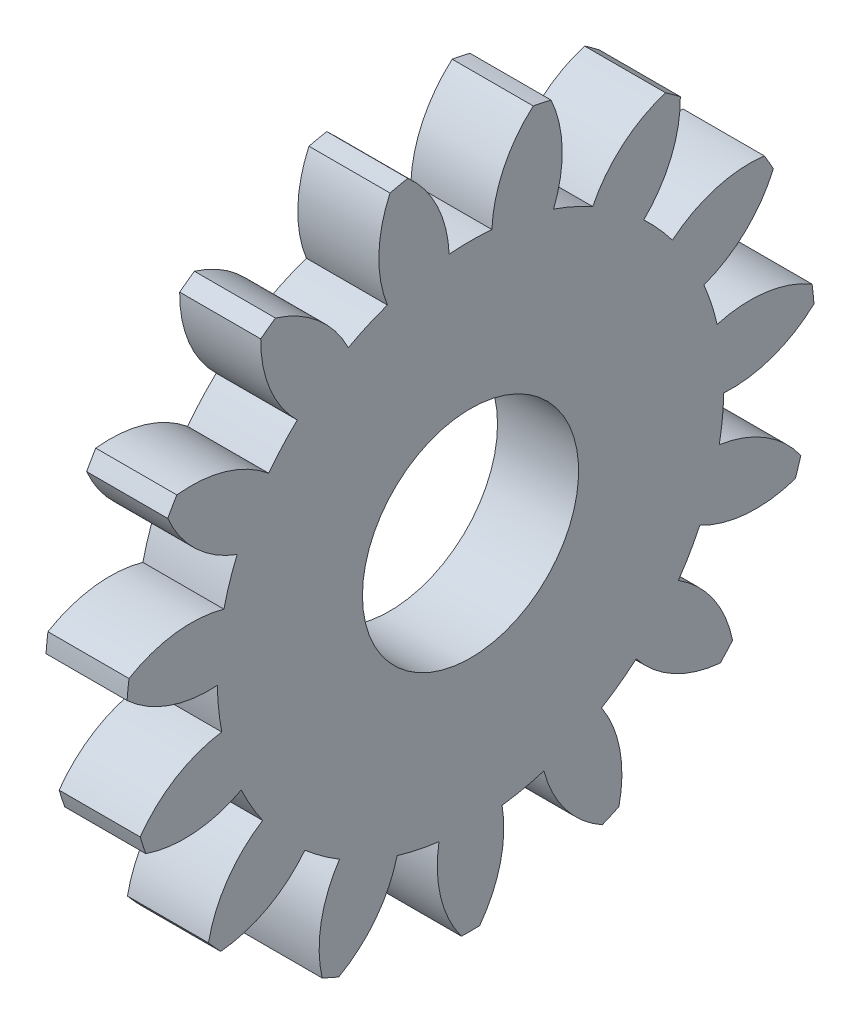
SolidWorks part; units mm, degrees
ref_plane "Plane1" through (0, 0, 0) normal (0, 0, 1) x (1, 0, 0)
ref_plane "Plane2" through (0, 0, 0) normal (0, 1, 0) x (1, 0, 0)
ref_plane "Plane3" through (0, 0, 0) normal (1, 0, 0) x (0, 0, -1)
sketch "HoldingSke" plane through (0, 0, 0) normal (0, 1, 0) x (1, 0, 0)
  line L0 (0, 0) -> (0.644, -0.1725)
  line L1 (-15, 0) -> (100, 0) construction
  line L2 (0, 0) -> (-2.1039, 2.3779)
  line L3 (0, 0) -> (-11.863, 4.5341)
  line L4 (0, 0) -> (8.3417, 2.2352)
  line L5 (0, 0) -> (-46.8476, -17.4728)
  line L6 (0, 0) -> (-2.4869, -1.6779)
  line L7 (-2.1039, 2.3779) -> (8.6586, 51.2059)
  line L8 (-76.2, 54.61) -> (-74.8, 54.61)
  line L9 (-71.009, 38.7566) -> (-53.1078, 45.2721)
  line L10 (-76.2, 71.12) -> (104.1128, 71.12)
  line L11 (0, 0) -> (-3, 0)
  line L12 (-76.2, 101.6) -> (-76.147, 101.6)
  line L13 (24.9733, 27.94) -> (52.9518, 28.4284)
  line L14 (24.9733, 27.94) -> (24.9743, 27.94)
  line L15 (24.9733, 27.94) -> (100.4006, 29.5858)
  line L16 (-63.627, -1.5) -> (-12.827, -1.5)
  circle A0 centre (0, 0) radius 4
  circle A1 centre (0, 0) radius 9.374
  circle A2 centre (0, 0) radius 37.5
  circle A3 centre (0, 0) radius 4
  dimension "MHD" = 18.748
  dimension "Hub_dia" = 75
  dimension "Bore" = 8
  dimension "MBD" = 8
  dimension "Num_teeth" = 15
  dimension "Pitch" = 0.6667
  dimension "Overall_len" = 50
  dimension "Show_teeth" = 15
  dimension "Thickness" = 3
  dimension "OAL" = 50.0001
  dimension "T_dim" = 1.4
  dimension "Ap" = 20
  dimension "H" = 19.05
  dimension "Pitch_radius" = 180.3128
  dimension "Width" = 3
  dimension "Backlash" = 0.053
  dimension "Addendum_fac" = 1
  dimension "Dedendum_fac" = 1.25
  dimension "Clearance_fac" = 0.25
  dimension "Dedendum_add" = 0.001
  dimension "Module" = 1.5
sketch "BasProSke" plane through (0, 0, 0) normal (0, 1, 0) x (1, 0, 0)
  line L0 (-10, 0) -> (60, 0) construction
  line L1 (0, 0) -> (0, 12.75)
  line L2 (0, 0) -> (3, 0)
  line L3 (3, 0) -> (3, 12.75)
  line L4 (3, 12.75) -> (0, 12.75)
  dimension "Thickness" = 3
  dimension "Diameter" = 25.5
revolve "Base-Revolve" add sketch "BasProSke" angle 360 about L0
sketch "TooCutSke" plane through (0, 0, 0) normal (1, 0, 0) x (0, 0, -1)
  line L1 (0, 0) -> (0, 107) construction
  line L2 (0, 0) -> (-1.2686, 11.1782) construction
  line L3 (0, 0) -> (-4.6563, 21.9061) construction
  line L4 (-1.2686, 11.1782) -> (-2.3281, 10.953) construction
  arc A0 (0.7915, 9.3405) -> (-0.7915, 9.3405) centre (0, 0) ccw
  arc A1 (2.3447, 12.5584) -> (-2.3447, 12.5584) centre (0, 0) ccw
  circle A2 centre (0, 0) radius 11.25 construction
  circle A3 centre (0, 0) radius 10.5715 construction
  arc A4 (-0.7915, 9.3405) -> (-2.3447, 12.5584) centre (-5.2877, 9.1541) ccw
  arc A5 (2.3447, 12.5584) -> (0.7915, 9.3405) centre (5.2877, 9.1541) ccw
  dimension "Root_dia" = 18.748
  dimension "Overcut_dia" = 25.5508
  dimension "Pitch_dia" = 22.5
  dimension "Base_dia" = 21.1431
  dimension "Flank_rad" = 4.5
  dimension "Half_ang" = 12
  dimension "Half_CT" = 1.0832
extrude "ToothCut" cut sketch "TooCutSke" along normal through all
fillet "Breaks" [suppressed] radius 0.03
fillet "RootFillets" [suppressed] radius 0.376
pattern_circular "TeethCuts" count 15 every 24 about axis through (-10, 0, 0) along (1, 0, 0) of "ToothCut", "RootFillets", "Breaks"
sketch "HubNeaOneSke" plane through (0, 0, 0) normal (-1, 0, 0) x (0, 0, 1)
  circle A0 centre (0, 0) radius 9.374
  dimension "Diameter" = 18.748
extrude "HubNearOne" [suppressed] add sketch "HubNeaOneSke" along normal blind 47.0001
sketch "HubNeaBotSke" plane through (0, 0, 0) normal (-1, 0, 0) x (0, 0, 1)
  circle A0 centre (0, 0) radius 9.374
  dimension "Diameter" = 18.748
extrude "HubNearBoth" [suppressed] add sketch "HubNeaBotSke" along normal blind 23.5
ref_plane "FarPln" through (3, 0, 0) normal (1, 0, 0) x (0, 0, -1)
sketch "HubFarSke" plane through (3, 0, 0) normal (1, 0, 0) x (0, 0, -1)
  circle A0 centre (0, 0) radius 9.374
  dimension "Diameter" = 18.748
extrude "HubFar" [suppressed] add sketch "HubFarSke" along normal blind 23.5
sketch "BorSke" plane through (0, 0, 0) normal (1, 0, 0) x (0, 0, -1)
  circle A0 centre (0, 0) radius 4
  dimension "Diameter" = 8
extrude "Bore" cut sketch "BorSke" along normal mid plane 100.0001
sketch "KeySke" plane through (0, 0, 0) normal (1, 0, 0) x (0, 0, -1)
  line L0 (-1.5, 0) -> (-1.5, 5.4)
  line L1 (-1.5, 5.4) -> (1.5, 5.4)
  line L2 (1.5, 5.4) -> (1.5, 0)
  line L3 (0, 0) -> (0, 34) construction
  line L4 (-1.5, 0) -> (1.5, 0)
  dimension "Width" = 3
  dimension "Offset" = 5.4
extrude "Keyway" [suppressed] cut sketch "KeySke" along normal mid plane 100.0001
pattern_circular "Keyway2" [suppressed] count 2 every 90 about axis through (-10, 0, 0) along (1, 0, 0)
equation "' \"Module@HoldingSke\" = 6.35"
equation "' \"Num_teeth@HoldingSke\" = 12"
equation "' \"Ap@HoldingSke\" =  20"
equation "' \"Ap@HoldingSke\" = 20"
equation "' \"Width@HoldingSke\" = 0.5 * 25.4"
equation "' \"Hub_dia@HoldingSke\"= 1 * 25.4"
equation "' \"Hub_dia@HoldingSke\" = 1 * 25.4"
equation "' \"Overall_len@HoldingSke\" = 1.0 * 25.4"
equation "' \"Bore@HoldingSke\" = 0.75 * 25.4"
equation "' \"T_dim@HoldingSke\" = 0.1 * 25.4"
equation "' \"Width@KeySke\" = 0.25 * 25.4"
equation "' \"Show_teeth@HoldingSke\" = 13"
equation "' \"Backlash@HoldingSke\" = 0.009 * 25.4"
equation "' \"Addendum_fac@HoldingSke\" = 1.0"
equation "' \"Dedendum_fac@HoldingSke\" = 1.25"
equation "' \"Dedendum_add@HoldingSke\" = 0.00005 * 25.4"
equation "' \"Clearance_fac@HoldingSke\" = 0.25"
equation "\"Pitch@HoldingSke\" = 1 / \"Module@HoldingSke\""
equation "\"Overcut_dia@TooCutSke\" = (\"Num_teeth@HoldingSke\" + 2 * \"Addendum_fac@HoldingSke\") / \"Pitch@HoldingSke\" + 0.002 * 25.4"
equation "\"Pitch_dia@TooCutSke\" = \"Num_teeth@HoldingSke\" / \"Pitch@HoldingSke\""
equation "\"Base_dia@TooCutSke\" = \"Num_teeth@HoldingSke\" / \"Pitch@HoldingSke\" * cos((\"Ap@HoldingSke\"  * 3.14159265 / 180))"
equation "\"Root_dia@TooCutSke\" = (\"Num_teeth@HoldingSke\" + 2) / \"Pitch@HoldingSke\" - 2 * (\"Addendum_fac@HoldingSke\" + \"Dedendum_fac@HoldingSke\") / \"Pitch@HoldingSke\" - \"Dedendum_add@HoldingSke\" * 2"
equation "\"Half_ang@TooCutSke\" = 180 / \"Num_teeth@HoldingSke\""
equation "\"Half_CT@TooCutSke\" = \"Num_teeth@HoldingSke\" / \"Pitch@HoldingSke\" * sin((3.14159265 / 2 / \"Num_teeth@HoldingSke\")) / 2 - 7 * \"Backlash@HoldingSke\" / 4"
equation "\"Flank_rad@TooCutSke\" = \"Num_teeth@HoldingSke\" / \"Pitch@HoldingSke\" / 5"
equation "\"Radius@RootFillets\" = \"Clearance_fac@HoldingSke\" / \"Pitch@HoldingSke\" + \"Dedendum_add@HoldingSke\""
equation "\"Break_rad@Breaks\" = 0.02 / \"Pitch@HoldingSke\""
equation "\"Thickness@HoldingSke\" = \"Width@HoldingSke\""
equation "\"OAL@HoldingSke\" = \"Thickness@HoldingSke\""
equation "\"MHD@HoldingSke\" = (\"Num_teeth@HoldingSke\" + 2) / \"Pitch@HoldingSke\" - 2 * (\"Addendum_fac@HoldingSke\" + \"Dedendum_fac@HoldingSke\")  / \"Pitch@HoldingSke\" - \"Dedendum_add@HoldingSke\" * 2"
equation "\"MBD@HoldingSke\" = (\"Num_teeth@HoldingSke\" + 2) / \"Pitch@HoldingSke\" - 2 * (\"Addendum_fac@HoldingSke\" + \"Dedendum_fac@HoldingSke\")  / \"Pitch@HoldingSke\" - \"Dedendum_add@HoldingSke\" * 2 - 0.002 * 25.4"
equation "\"MHD@HoldingSke\" = ((sgn( \"MHD@HoldingSke\" - \"Hub_dia@HoldingSke\" )-1)*( \"MHD@HoldingSke\" - \"Hub_dia@HoldingSke\" ))/-2+ \"Hub_dia@HoldingSke\""
equation "\"MBD@HoldingSke\" = ((sgn( \"MBD@HoldingSke\" - \"Bore@HoldingSke\" )-1)*( \"MBD@HoldingSke\" - \"Bore@HoldingSke\" ))/-2+ \"Bore@HoldingSke\""
equation "\"OAL@HoldingSke\" = ((sgn( \"OAL@HoldingSke\" - \"Overall_len@HoldingSke\" )+1)*( \"OAL@HoldingSke\" - \"Overall_len@HoldingSke\" ))/2 + \"Overall_len@HoldingSke\" + 0.000002 * 25.4"
equation "\"Num_teeth@TeethCuts\" = int( \"Show_teeth@HoldingSke\" ) + 1"
equation "\"Num_teeth@TeethCuts\" = ((sgn( \"Num_teeth@TeethCuts\" - \"Num_teeth@HoldingSke\" )-1)*( \"Num_teeth@TeethCuts\" - \"Num_teeth@HoldingSke\" ))/-2+ \"Num_teeth@HoldingSke\""
equation "\"Num_teeth@TeethCuts\" = ((sgn( \"Num_teeth@TeethCuts\" - 2.0)+1)*( \"Num_teeth@TeethCuts\" - 2.0))/2 +2.0"
equation "\"Angle@TeethCuts\" = 360.0 / \"Num_teeth@HoldingSke\""
equation "\"Diameter@BasProSke\" = (\"Num_teeth@HoldingSke\" + 2 * \"Addendum_fac@HoldingSke\") / \"Pitch@HoldingSke\""
equation "\"Thickness@BasProSke\"  = \"Thickness@HoldingSke\""
equation "' \"Fillet_rad@BasProSke\" =  \"Thickness@HoldingSke\" * 0.05"
equation "' \"Fillet_rad@BasProSke\" = \"Thickness@HoldingSke\" * 0.05"
equation "\"MHD@HoldingSke\" = ((sgn( \"MHD@HoldingSke\" - \"Root_dia@TooCutSke\" )-1)*( \"MHD@HoldingSke\" - \"Root_dia@TooCutSke\" ))/-2+ \"Root_dia@TooCutSke\""
equation "\"Diameter@HubNeaOneSke\" = \"MHD@HoldingSke\""
equation "\"Length@HubNearOne\" = \"OAL@HoldingSke\" - \"Thickness@BasProSke\""
equation "\"Diameter@HubNeaBotSke\" = \"MHD@HoldingSke\""
equation "\"Length@HubNearBoth\" = ( \"OAL@HoldingSke\" - \"Thickness@BasProSke\" ) / 2.0"
equation "\"Thickness@FarPln\" = \"Thickness@BasProSke\""
equation "\"Diameter@HubFarSke\" = \"MHD@HoldingSke\""
equation "\"Length@HubFar\" = ( \"OAL@HoldingSke\" - \"Thickness@BasProSke\" ) / 2.0"
equation "\"Diameter@BorSke\" = \"MBD@HoldingSke\""
equation "\"D1@Bore\" = \"OAL@HoldingSke\" * 2.0"
equation "\"D1@Keyway\" = \"OAL@HoldingSke\" * 2.0"
equation "\"Offset@KeySke\" = \"T_dim@HoldingSke\" + \"MBD@HoldingSke\" / 2.0"
